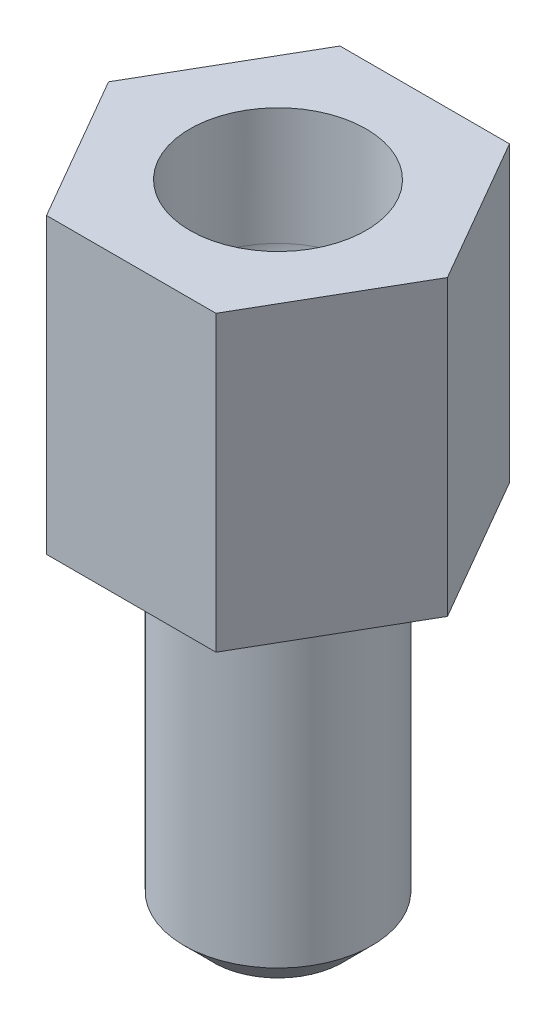
SolidWorks part; units mm, degrees
material "Alloy Steel"
ref_plane "Front Plane" through (0, 0, 0) normal (0, 0, 1) x (1, 0, 0)
ref_plane "Top Plane" through (0, 0, 0) normal (0, 1, 0) x (1, 0, 0)
ref_plane "Right Plane" through (0, 0, 0) normal (1, 0, 0) x (0, 0, -1)
sketch "Sketch1" plane through (0, 0, 0) normal (0, 1, 0) x (1, 0, 0)
  line L0 (0, 0) -> (0, 2.5) construction
  line L1 (-1.4434, 2.5) -> (1.4434, 2.5)
  line L2 (1.4434, 2.5) -> (2.8868, 0)
  line L3 (2.8868, 0) -> (1.4434, -2.5)
  line L4 (1.4434, -2.5) -> (-1.4434, -2.5)
  line L5 (-1.4434, -2.5) -> (-2.8868, 0)
  line L6 (-2.8868, 0) -> (-1.4434, 2.5)
  circle A0 centre (0, 0) radius 1.5
  dimension "D2" = 3
  dimension "D1" = 5
  dimension "D3" = 2.5
extrude "Extrude1" add sketch "Sketch1" along normal blind 5
sketch "Sketch2" plane through (0, 0, 0) normal (0, -1, 0) x (1, 0, 0)
  circle A0 centre (0, 0) radius 1.6
  dimension "D1" = 3.2
extrude "Extrude2" add sketch "Sketch2" along normal blind 6 and the other way blind 2
chamfer "Chamfer1" distance 0.5 angle 45 1 edges at (0, -6, -1.6)
fillet "Fillet1" radius 0.5 1 edges at (0, 0, 1.6)
fillet "Fillet2" radius 1 1 edges at (0, 2, -1.5)
